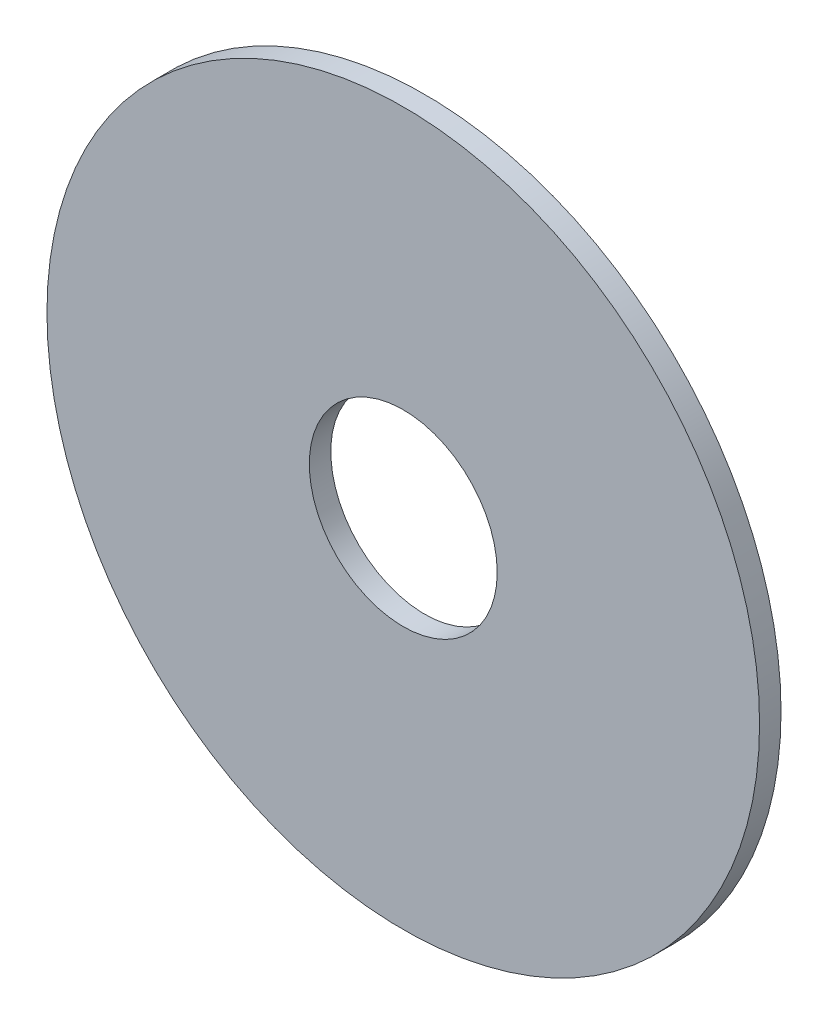
SolidWorks part; units mm, degrees
material "6061 Alloy"
ref_plane "Front Plane" through (0, 0, 0) normal (0, 0, 1) x (1, 0, 0)
ref_plane "Top Plane" through (0, 0, 0) normal (0, 1, 0) x (1, 0, 0)
ref_plane "Right Plane" through (0, 0, 0) normal (1, 0, 0) x (0, 0, -1)
sketch "Sketch1" plane through (0, 0, 0) normal (0, 0, 1) x (-1, 0, 0)
  circle A0 centre (-4.2545, -4.5968) radius 17.5
  circle A1 centre (-4.2545, -4.5968) radius 66.37
extrude "Boss-Extrude1" add sketch "Sketch1" along normal blind 4
